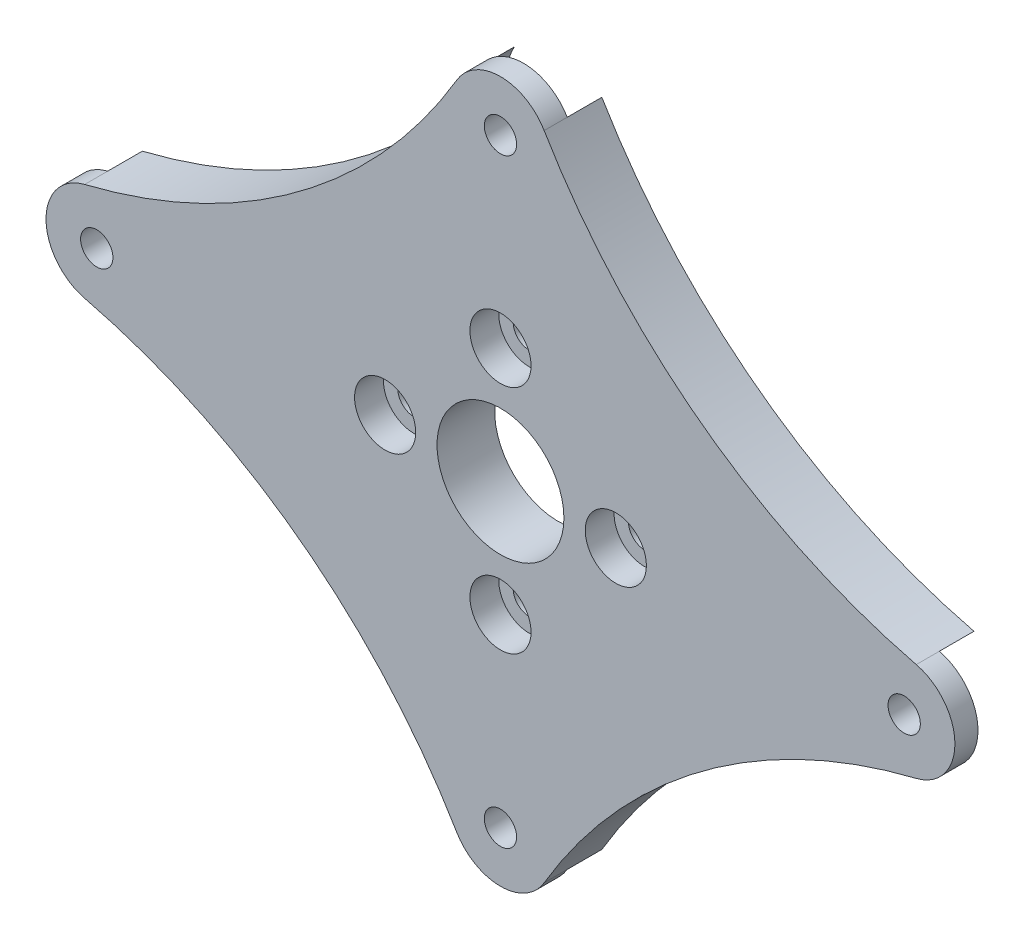
SolidWorks part; units mm, degrees
ref_plane "Front Plane" through (0, 0, 0) normal (0, 0, 1) x (1, 0, 0)
ref_plane "Top Plane" through (0, 0, 0) normal (0, 1, 0) x (1, 0, 0)
ref_plane "Right Plane" through (0, 0, 0) normal (1, 0, 0) x (0, 0, -1)
sketch "Sketch1" plane through (0, 0, 0) normal (0, 0, 1) x (1, 0, 0)
  line L0 (0, -26) -> (0, 26) construction
  line L1 (-35, 0) -> (35, 0) construction
  line L2 (0, 26) -> (35, 0) construction
  circle A0 centre (0, 0) radius 5.5
  circle A1 centre (0, 0) radius 10 construction
  circle A2 centre (0, 10) radius 1.4
  circle A3 centre (10, 0) radius 1.4
  circle A4 centre (0, -10) radius 1.4
  circle A5 centre (-10, 0) radius 1.4
  circle A6 centre (35, 0) radius 1.4
  circle A7 centre (0, 26) radius 1.4
  circle A8 centre (0, -26) radius 1.4
  circle A9 centre (-35, 0) radius 1.4
  arc A10 (-3.7884, 28.2379) -> (3.7884, 28.2379) centre (0, 26) cw
  arc A11 (36.0485, 4.2733) -> (36.0485, -4.2733) centre (35, 0) cw
  arc A12 (3.7884, 28.2379) -> (36.0485, 4.2733) centre (48.393, 54.5867) ccw
  arc A13 (3.7884, -28.2379) -> (-3.7884, -28.2379) centre (0, -26) cw
  arc A14 (-3.7884, -28.2379) -> (-36.0485, -4.2733) centre (-48.393, -54.5867) ccw
  arc A15 (-36.0485, -4.2733) -> (-36.0485, 4.2733) centre (-35, 0) cw
  arc A16 (-3.7884, 28.2379) -> (-36.0485, 4.2733) centre (-48.393, 54.5867) cw
  arc A17 (3.7884, -28.2379) -> (36.0485, -4.2733) centre (48.393, -54.5867) cw
  point P15 (0, 0)
  point P18 (0, 0)
  dimension "D1" = 11
  dimension "D2" = 20
  dimension "D3" = 2.8
  dimension "D4" = 2.8
  dimension "D5" = 3
  dimension "D6" = 3
  dimension "D7" = 52
  dimension "D8" = 70
  dimension "D9" = 2
extrude "Boss-Extrude1" add sketch "Sketch1" along normal blind 5
sketch "Sketch2" plane through (0, 0, 5) normal (0, 0, 1) x (1, 0, 0)
  circle A0 centre (0, 10) radius 2.65
  circle A1 centre (10, 0) radius 2.65
  circle A2 centre (0, -10) radius 2.65
  circle A3 centre (-10, 0) radius 2.65
  dimension "D1" = 5.3
extrude "Cut-Extrude1" cut sketch "Sketch2" against normal blind 2.5
sketch "Sketch3" plane through (0, 0, 0) normal (0, 0, -1) x (-1, 0, 0)
  circle A0 centre (0, 26) radius 4.4
  circle A1 centre (35, 0) radius 4.4
  circle A2 centre (0, -26) radius 4.4
  circle A3 centre (-35, 0) radius 4.4
  arc A4 (-36.0485, 4.2733) -> (-36.0485, -4.2733) centre (-35, 0) ccw construction
extrude "Cut-Extrude2" cut sketch "Sketch3" against normal blind 3
